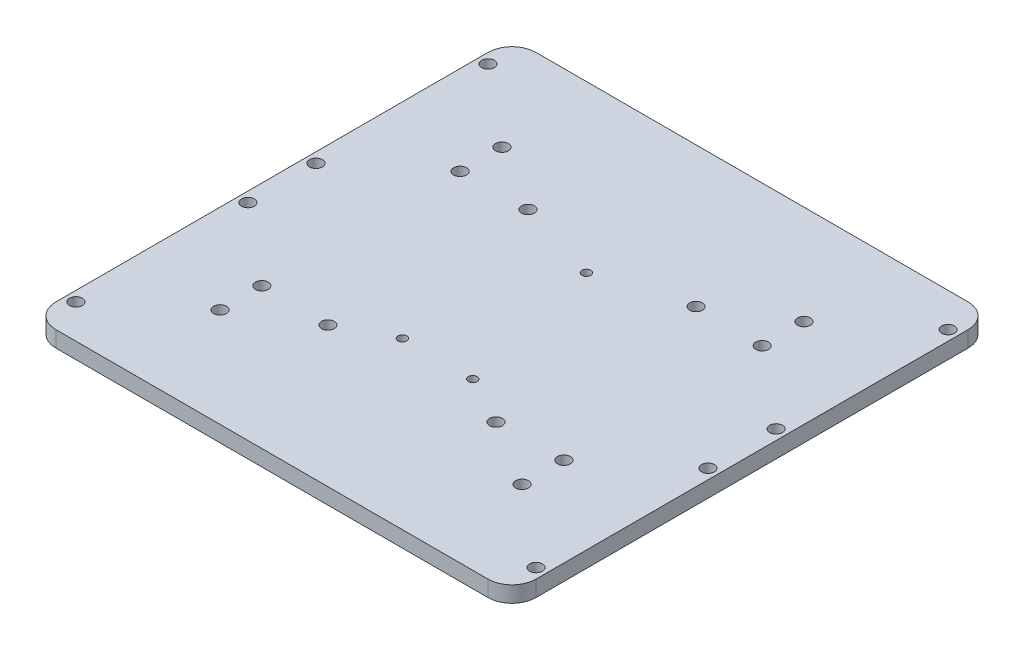
SolidWorks part; units mm, degrees
material "自定义塑料"
ref_plane "前视基准面" through (0, 0, 0) normal (0, 0, 1) x (1, 0, 0)
ref_plane "上视基准面" through (0, 0, 0) normal (0, 1, 0) x (1, 0, 0)
ref_plane "右视基准面" through (0, 0, 0) normal (1, 0, 0) x (0, 0, -1)
sketch "草图1" plane through (0, 0, 0) normal (0, 1, 0) x (1, 0, 0)
  line L0 (0, 0) -> (-20.2314, 0) construction
  line L1 (-54, 60) -> (54, 60)
  line L2 (-60, 54) -> (-60, -54)
  line L3 (-54, -60) -> (54, -60)
  line L4 (60, 54) -> (60, -54)
  line L5 (-60, 60) -> (60, -60) construction
  line L6 (-60, -60) -> (60, 60) construction
  line L7 (0, 0) -> (0, 21.0425) construction
  line L8 (-60, 30) -> (-53.3899, 30) construction
  circle A0 centre (-57.5, 51.5) radius 1.6
  circle A1 centre (-57.5, 8.5) radius 1.6
  circle A2 centre (-37.75, 35.23) radius 1.6
  circle A3 centre (-37.75, 24.77) radius 1.6
  circle A4 centre (-57.5, -8.5) radius 1.6
  circle A5 centre (-37.75, -24.77) radius 1.6
  circle A6 centre (-37.75, -35.23) radius 1.6
  circle A7 centre (-57.5, -51.5) radius 1.6
  circle A8 centre (57.5, -51.5) radius 1.6
  circle A9 centre (37.75, -35.23) radius 1.6
  circle A10 centre (37.75, -24.77) radius 1.6
  circle A11 centre (57.5, -8.5) radius 1.6
  circle A12 centre (57.5, 8.5) radius 1.6
  circle A13 centre (37.75, 24.77) radius 1.6
  circle A14 centre (37.75, 35.23) radius 1.6
  circle A15 centre (57.5, 51.5) radius 1.6
  circle A16 centre (0, 18.6) radius 1.1
  circle A17 centre (8.8, -18.6) radius 1.1
  circle A18 centre (-8.8, -18.6) radius 1.1
  circle A19 centre (-21, 25) radius 1.6
  circle A20 centre (21, 25) radius 1.6
  circle A21 centre (21, -25) radius 1.6
  circle A22 centre (-21, -25) radius 1.6
  arc A23 (-60, -54) -> (-54, -60) centre (-54, -54) ccw
  arc A24 (54, -60) -> (60, -54) centre (54, -54) ccw
  arc A25 (-54, 60) -> (-60, 54) centre (-54, 54) ccw
  arc A26 (54, 60) -> (60, 54) centre (54, 54) cw
  point P0 (0, 0)
  dimension "D4" = 3.2
  dimension "D9" = 2.2
  dimension "D15" = 3.2
  dimension "D16" = 6
  dimension "D1" = 120
  dimension "D2" = 120
  dimension "D3" = 30
  dimension "D5" = 43
  dimension "D6" = 2.5
  dimension "D7" = 10.46
  dimension "D8" = 19.75
  dimension "D10" = 18.6
  dimension "D11" = 18.6
  dimension "D12" = 8.8
  dimension "D13" = 42
  dimension "D14" = 50
extrude "凸台-拉伸1" add sketch "草图1" along normal blind 4
